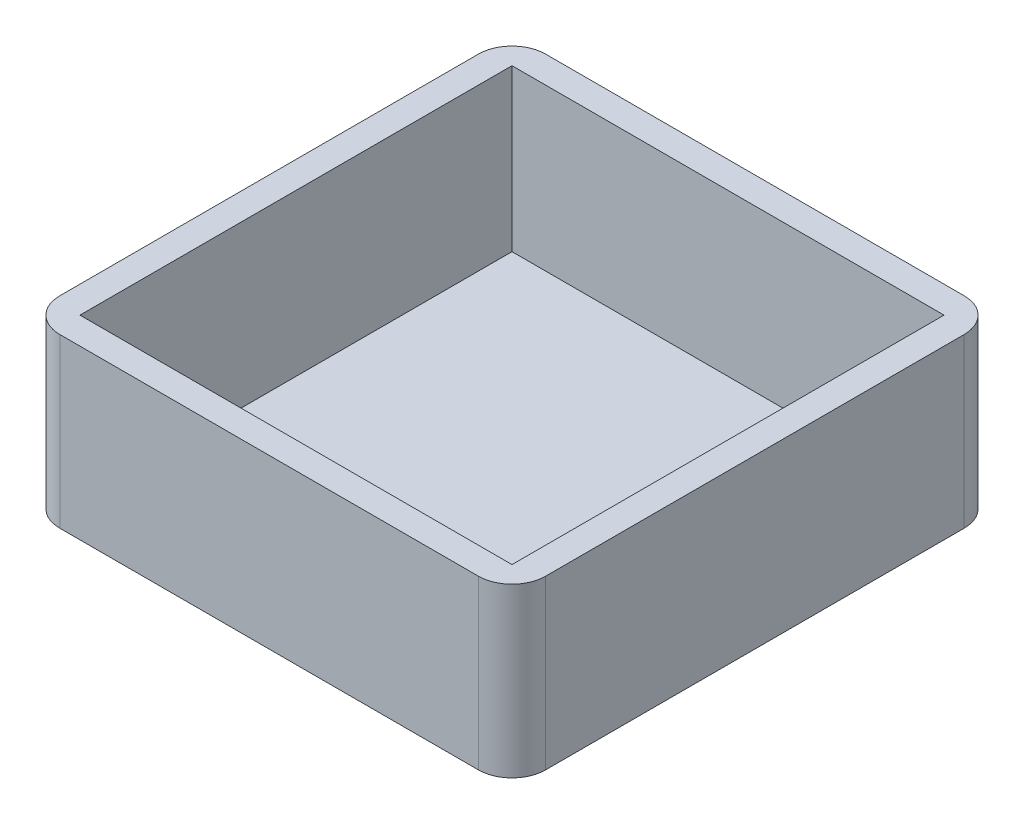
SolidWorks part; units mm, degrees
ref_plane "Front Plane" through (0, 0, 0) normal (0, 0, 1) x (1, 0, 0)
ref_plane "Top Plane" through (0, 0, 0) normal (0, 1, 0) x (1, 0, 0)
ref_plane "Right Plane" through (0, 0, 0) normal (1, 0, 0) x (0, 0, -1)
sketch "Sketch1" plane through (0, 0, 0) normal (0, 1, 0) x (1, 0, 0)
  line L1 (-72.376, -72.376) -> (72.376, -72.376)
  line L2 (-72.376, -72.376) -> (-72.376, 72.376)
  line L3 (-72.376, 72.376) -> (72.376, 72.376)
  line L4 (72.376, -72.376) -> (72.376, 72.376)
  line L5 (-72.376, -72.376) -> (72.376, 72.376) construction
  line L6 (-72.376, 72.376) -> (72.376, -72.376) construction
  point P0 (0, 0)
extrude "Boss-Extrude1" add sketch "Sketch1" along normal blind 50
sketch "Sketch2" plane through (0, 50, 0) normal (0, 1, 0) x (1, 0, 0)
  line L0 (72.376, 72.376) -> (-72.376, 72.376) construction
  line L1 (-64.376, -64.376) -> (64.376, -64.376)
  line L2 (-64.376, -64.376) -> (-64.376, 64.376)
  line L3 (-64.376, 64.376) -> (64.376, 64.376)
  line L4 (64.376, -64.376) -> (64.376, 64.376)
  line L5 (-64.376, -64.376) -> (64.376, 64.376) construction
  line L6 (-64.376, 64.376) -> (64.376, -64.376) construction
  point P0 (0, 0)
  dimension "D1" = 8
extrude "Cut-Extrude1" cut sketch "Sketch2" against normal offset from surface (48 mm away) 2 up to face at (0, 0, 0)
fillet "Fillet1" radius 10 4 edges at (-72.376, 25, -72.376) (72.376, 25, -72.376) (72.376, 25, 72.376) (-72.376, 25, 72.376)
